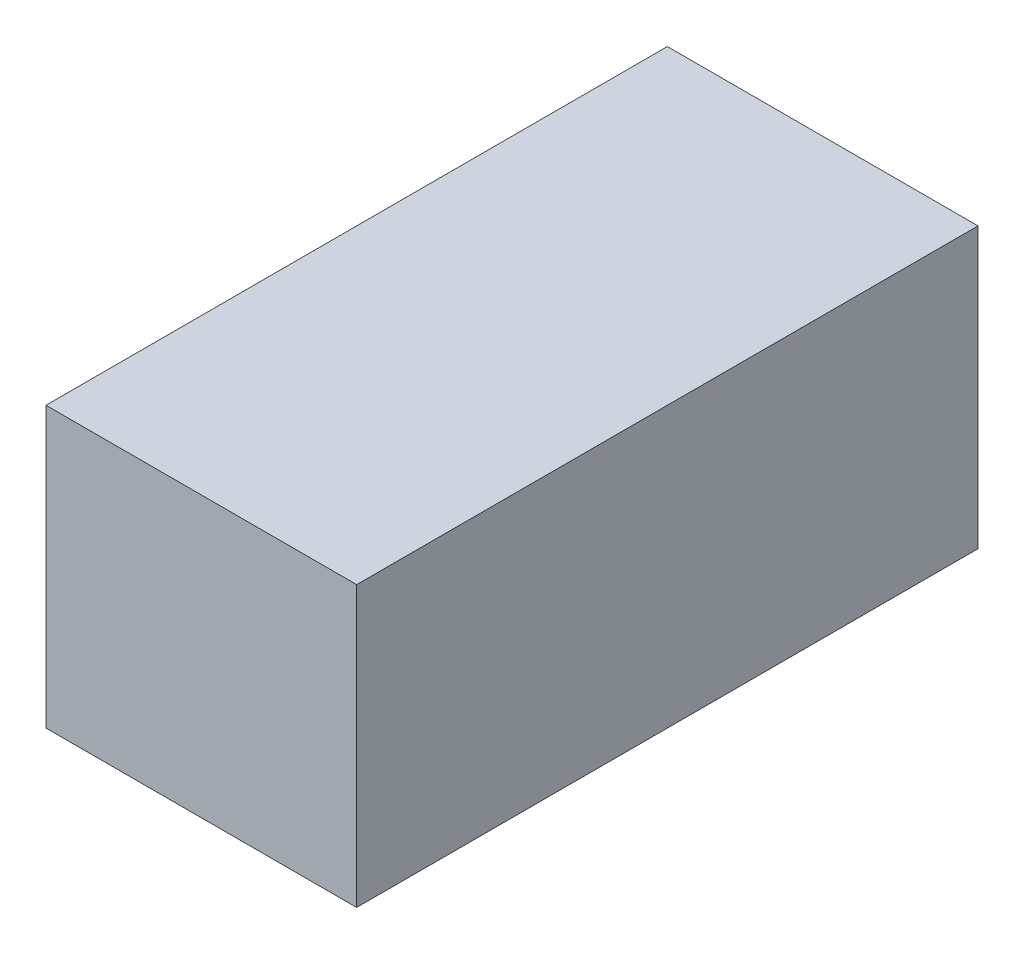
SolidWorks part; units mm, degrees
ref_plane "Front Plane" through (0, 0, 0) normal (0, 0, 1) x (1, 0, 0)
ref_plane "Top Plane" through (0, 0, 0) normal (0, 1, 0) x (1, 0, 0)
ref_plane "Right Plane" through (0, 0, 0) normal (1, 0, 0) x (0, 0, -1)
sketch "Sketch1" plane through (0, 0, 0) normal (0, 0, 1) x (1, 0, 0)
  line L1 (-100, -90) -> (100, -90)
  line L2 (-100, -90) -> (-100, 90)
  line L3 (-100, 90) -> (100, 90)
  line L4 (100, -90) -> (100, 90)
  line L5 (-100, -90) -> (100, 90) construction
  line L6 (-100, 90) -> (100, -90) construction
  point P0 (0, 0)
  dimension "D1" = 180
  dimension "D2" = 200
extrude "Boss-Extrude1" add sketch "Sketch1" along normal blind 400
